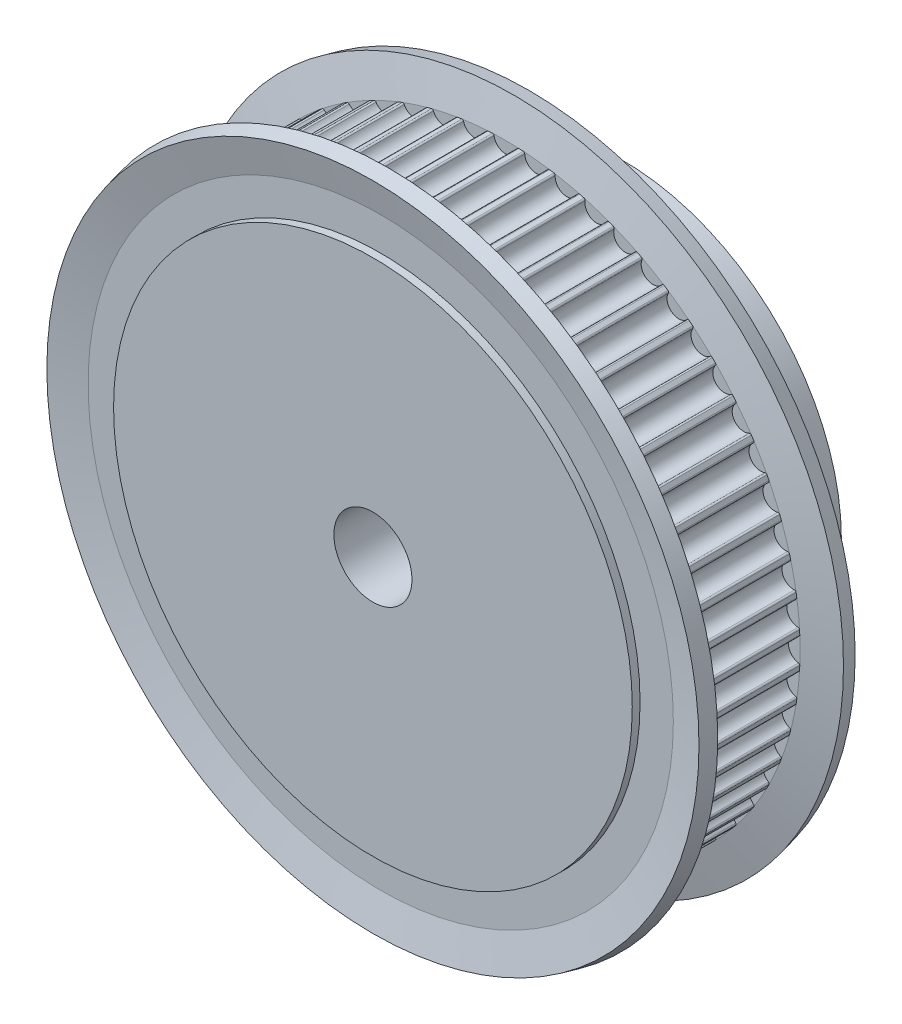
SolidWorks part; units mm, degrees
material "5052-H32"
ref_plane "Front Plane" through (0, 0, 0) normal (0, 0, 1) x (1, 0, 0)
ref_plane "Top Plane" through (0, 0, 0) normal (0, 1, 0) x (1, 0, 0)
ref_plane "Right Plane" through (0, 0, 0) normal (1, 0, 0) x (0, 0, -1)
sketch "Sketch1" plane through (0, 0, 0) normal (0, 0, 1) x (1, 0, 0)
  line L0 (-0.9868, 18.8284) -> (0, 0) construction
  line L1 (0, 0) -> (0.9868, 18.8284) construction
  circle A0 centre (0, 0) radius 21.1083
  circle A1 centre (0, 0) radius 19.1083 construction
  arc A2 (0.9868, 18.8284) -> (0.8456, 18.8353) centre (0, 0) ccw
  arc A3 (-0.8456, 18.8353) -> (-0.9868, 18.8284) centre (0, 0) ccw
  arc A4 (-0.7421, 18.7499) -> (0.7421, 18.7499) centre (0, 18.8583) ccw
  arc A5 (-0.7498, 18.8394) -> (0.7498, 18.8394) centre (0, 0) ccw construction
  arc A6 (0.7421, 18.7499) -> (0.8456, 18.8353) centre (0.8411, 18.7354) cw
  arc A7 (-0.7421, 18.7499) -> (-0.8456, 18.8353) centre (-0.8411, 18.7354) ccw
  circle A8 centre (0, 0) radius 18.8543
  circle A9 centre (0, 0) radius 2.5
  dimension "D1" = 38.2166
  dimension "D3" = 0.75
  dimension "D8" = 5
  dimension "D2" = 2
  dimension "D4" = 18.8583
  dimension "D6" = 0.254
  dimension "D5" = 6
sketch "Sketch4" plane through (0, 0, 0) normal (1, 0, 0) x (0, 0, -1)
  line L6 (-5.15, 0) -> (5.15, 0) construction
  line L7 (-5, 16.6083) -> (-5, 21.1083) construction
  line L8 (-5, 21.1083) -> (5, 21.1083) construction
  line L9 (5, 16.6083) -> (5, 21.1083) construction
  line L13 (0, 21.1083) -> (0, -21.1083) construction
  line L14 (-5, 16.6083) -> (5, 16.6083)
  line L15 (-3.5, 16.6083) -> (-3.5, 18.8543)
  line L16 (-3.5, 18.8543) -> (-4.0262, 21.1083)
  line L17 (-4.0262, 21.1083) -> (-5, 20.8809)
  line L18 (-5, 20.8809) -> (-4.5, 18.7391)
  line L19 (-4.5, 18.7391) -> (-4.5, 16.6083)
  line L24 (0, 55) -> (0, -55) construction
  line L25 (5, 2.5) -> (-5, 2.5)
  line L26 (5, 2.5) -> (5, 16.6083)
  line L27 (5, 16.6083) -> (-5, 16.6083)
  line L28 (-5, 2.5) -> (-5, 16.6083)
  line L29 (-5, 16.6083) -> (5, 16.6083)
  line L30 (4.0262, 21.1083) -> (5, 20.8809)
  line L31 (5, 2.5) -> (11, 2.5)
  line L32 (5, 2.5) -> (5, 14)
  line L33 (5, 14) -> (11, 14)
  line L34 (11, 2.5) -> (11, 14)
  line L35 (5, 20.8809) -> (4.5, 18.7391)
  line L36 (3.5, 18.8543) -> (4.0262, 21.1083)
  line L37 (3.5, 16.6083) -> (3.5, 18.8543)
  line L38 (4.5, 18.7391) -> (4.5, 16.6083)
  line L40 (-4.5, 16.6083) -> (-3.5, 16.6083)
  line L41 (3.5, 16.6083) -> (4.5, 16.6083)
  line L42 (-3.5, 18.8543) -> (3.5, 18.8543)
  line L43 (-3.5, 18.8543) -> (-3.5, 16.6083)
  line L44 (-3.5, 16.6083) -> (3.5, 16.6083)
  line L45 (3.5, 18.8543) -> (3.5, 16.6083)
  point P10 (0, 21.1083)
  dimension "D2" = 4.5
  dimension "D3" = 1.5
  dimension "D4" = 1
  dimension "D5" = 1
  dimension "D6" = 18.8543
  dimension "D7" = 2.5
  dimension "D8" = 16
  dimension "D9" = 14
  dimension "D1" = 7
revolve "Revolve1" add sketch "Sketch4" angle 360 about L6
extrude "Cut-Extrude3" cut sketch "Sketch1" against normal mid plane 7 contours A6 A8 A7 A4
pattern_circular "CirPattern2" count 60 over 360 about axis through (0, 0, 0) along (0, 0, 1) of "Cut-Extrude3"
sketch "Sketch5" plane through (0, 0, 0) normal (0, 1, 0) x (1, 0, 0)
  line L1 (14, 11) -> (-14, 11) construction
  circle A0 centre (0, 7) radius 1.25
  dimension "D1" = 2.5
  dimension "D2" = 4
hole_wizard "M3 Tapped Hole1" positions "Sketch6" profile "Sketch7" tap size "M3" standard "ISO"
sketch "Sketch6" plane through (0, 0, 0) normal (0, 1, 0) x (1, 0, 0)
  point P0 (0, 7)
sketch "Sketch7" plane through (0, 0, -7) normal (1, 0, 0) x (0, 0, -1)
  line L0 (0, 0) -> (0, 21.1083)
  line L1 (0, 21.1083) -> (1.25, 21.1083)
  line L2 (1.25, 21.1083) -> (1.25, 0)
  line L5 (1.25, 0) -> (0, 0)
  line L11 (0, -6.35) -> (0, 107.95) construction
  dimension "Thru Tap Drill Dia." = 2.5
  dimension "Thru Tap Drill Depth" = 21.1083
cosmetic thread "Hole Thread1" parameters "D2"=3
pattern_circular "CirPattern3" count 2 over 120 about axis through (0, 0, 5.15) along (0, 0, 1) of "M3 Tapped Hole1"
equation "\"D1@Sketch1\"= \"Teeth\" * 2 / 3.14"
equation "\"Teeth\"= 60"
equation "\"D4@Sketch1\"=\"D1@Sketch1\"/2 -0.25"
equation "\"D5@Sketch1\"=360/\"Teeth\""
equation "\"Shank Dia D\"= 28"
equation "\"Shaft Dia\"= 5"
equation "\"D8@Sketch1\"=\"Shaft Dia\""
equation "\"Width Teeth A\"= 7"
equation "\"Overal Width L\"= 16"
equation "\"D6@Sketch4\"=\"Teeth\"/3.14 - 0.254"
equation "\"D7@Sketch4\"=\"Shaft Dia\"/2"
equation "\"D8@Sketch4\"=\"Overal Width L\""
equation "\"D9@Sketch4\"=\"Shank Dia D\"/2"
equation "\"D1@Sketch4\"=\"Width Teeth A\""
